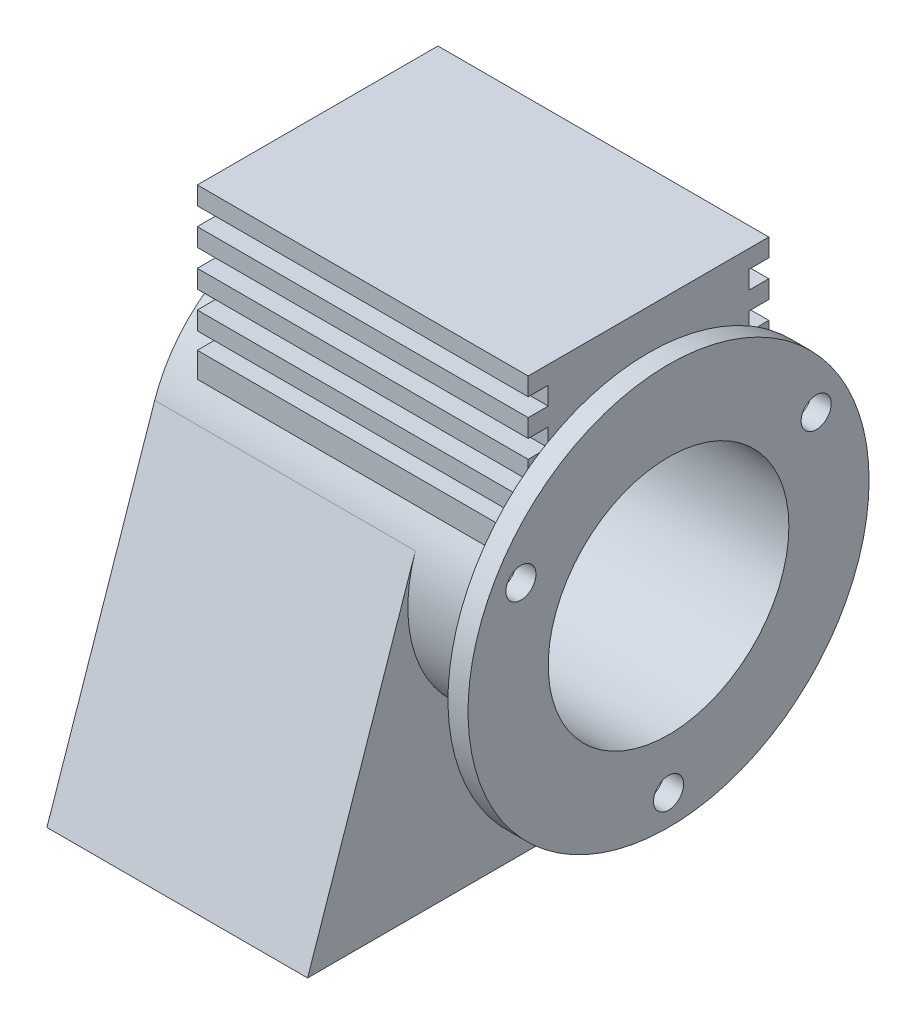
SolidWorks part; units mm, degrees
material "356.0-T6 Permanent Mold cast (SS)"
ref_plane "Front Plane" through (0, 0, 0) normal (0, 0, 1) x (1, 0, 0)
ref_plane "Top Plane" through (0, 0, 0) normal (0, 1, 0) x (1, 0, 0)
ref_plane "Right Plane" through (0, 0, 0) normal (1, 0, 0) x (0, 0, -1)
sketch "Sketch2" plane through (0, 0, 0) normal (1, 0, 0) x (0, 0, -1)
  line L0 (-152.4, -171.45) -> (152.4, -171.45)
  line L1 (0, 287.9559) -> (0, -287.9559) construction
  line L2 (-152.4, -171.45) -> (-84.1413, 28.6959)
  line L3 (152.4, -171.45) -> (84.1413, 28.6959)
  circle A0 centre (0, 0) radius 88.9
  circle A1 centre (0, 0) radius 19.05
  point P7 (0, -171.45)
  point P9 (0, 0)
  dimension "D1" = 177.8
  dimension "D2" = 38.1
  dimension "D3" = 304.8
  dimension "D4" = 171.45
extrude "Boss-Extrude1" add sketch "Sketch2" against normal blind 165.1 contours L1 A0 L2 L0 | A0 L1 L0 L3 | L1 A0 A1 | A0 L1 A1
sketch "Sketch3" plane through (0, 0, 0) normal (1, 0, 0) x (0, 0, -1)
  circle A0 centre (0, 0) radius 88.9
  circle A1 centre (0, 0) radius 16.51
  dimension "D1" = 177.8
  dimension "D2" = 33.02
extrude "Boss-Extrude2" add sketch "Sketch3" along normal blind 63.5
sketch "Sketch6" plane through (0, 0, 0) normal (1, 0, 0) x (0, 0, -1)
  line L0 (0, -279.2098) -> (0, 279.2098) construction
  line L1 (76.2, 152.4) -> (-76.2, 152.4)
  line L2 (-76.2, 152.4) -> (-76.2, 140.97)
  line L3 (-76.2, 140.97) -> (-63.5, 140.97)
  line L4 (-63.5, 140.97) -> (-63.5, 129.54)
  line L5 (-63.5, 129.54) -> (-76.2, 129.54)
  line L6 (-76.2, 129.54) -> (-76.2, 118.11)
  line L7 (-76.2, 118.11) -> (-63.5, 118.11)
  line L8 (-63.5, 118.11) -> (-63.5, 106.68)
  line L9 (-63.5, 106.68) -> (-76.2, 106.68)
  line L10 (-76.2, 106.68) -> (-76.2, 95.25)
  line L11 (-76.2, 95.25) -> (-63.5, 95.25)
  line L12 (-217.0156, 0) -> (217.0156, 0) construction
  line L13 (-63.5, 95.25) -> (-63.5, 83.82)
  line L14 (-63.5, 83.82) -> (-76.2, 83.82)
  line L15 (-76.2, 83.82) -> (-76.2, 72.39)
  line L16 (-76.2, 72.39) -> (-63.5, 72.39)
  line L17 (-63.5, 72.39) -> (-63.5, 61.722)
  line L18 (-63.5, 61.722) -> (-76.2, 61.722)
  line L19 (-76.2, 61.722) -> (-76.2, 0)
  line L20 (76.2, 152.4) -> (76.2, 140.97)
  line L21 (76.2, 140.97) -> (63.5, 140.97)
  line L22 (63.5, 140.97) -> (63.5, 129.54)
  line L23 (63.5, 129.54) -> (76.2, 129.54)
  line L24 (76.2, 129.54) -> (76.2, 118.11)
  line L25 (76.2, 118.11) -> (63.5, 118.11)
  line L26 (63.5, 118.11) -> (63.5, 106.68)
  line L27 (63.5, 106.68) -> (76.2, 106.68)
  line L28 (76.2, 106.68) -> (76.2, 95.25)
  line L29 (76.2, 95.25) -> (63.5, 95.25)
  line L30 (63.5, 95.25) -> (63.5, 83.82)
  line L31 (63.5, 83.82) -> (76.2, 83.82)
  line L32 (76.2, 83.82) -> (76.2, 72.39)
  line L33 (76.2, 72.39) -> (63.5, 72.39)
  line L34 (63.5, 72.39) -> (63.5, 61.722)
  line L35 (76.2, 61.722) -> (76.2, 0)
  line L36 (63.5, 61.722) -> (76.2, 61.722)
  line L37 (-76.2, 0) -> (76.2, 0)
  point P5 (0, 0)
  point P21 (0, 0)
  point P27 (0, 0)
  point P30 (0, 152.4)
  dimension "D1" = 11.43
  dimension "D2" = 11.43
  dimension "D3" = 11.43
  dimension "D4" = 12.7
  dimension "D5" = 12.7
  dimension "D6" = 12.7
  dimension "D7" = 12.7
  dimension "D8" = 22.86
  dimension "D9" = 22.86
  dimension "D10" = 61.722
  dimension "D11" = 76.2
  dimension "D12" = 12.7
  dimension "D13" = 12.7
  dimension "D14" = 152.4
  dimension "D15" = 12.7
  dimension "D18" = 11.43
  dimension "D21" = 22.86
extrude "Boss-Extrude3" add sketch "Sketch6" against normal blind 209.55 from offset 63.5
sketch "Sketch7" plane through (63.5, 0, 0) normal (1, 0, 0) x (0, 0, -1)
  circle A1 centre (0, 0) radius 127
  circle A2 centre (0, 0) radius 107.95 construction
  circle A3 centre (0, -107.95) radius 9.525
  circle A4 centre (-93.4874, 53.975) radius 9.525
  circle A5 centre (93.4874, 53.975) radius 9.525
  point P13 (0, 0)
  dimension "D1" = 254
  dimension "D2" = 215.9
  dimension "D3" = 19.05
  dimension "D4" = 3
extrude "Boss-Extrude4" add sketch "Sketch7" along normal blind 12.7
sketch "Sketch8" plane through (76.2, 0, 0) normal (1, 0, 0) x (0, 0, -1)
  circle A0 centre (0, 0) radius 76.2
  dimension "D1" = 152.4
extrude "Cut-Extrude1" cut sketch "Sketch8" against normal blind 228.6
